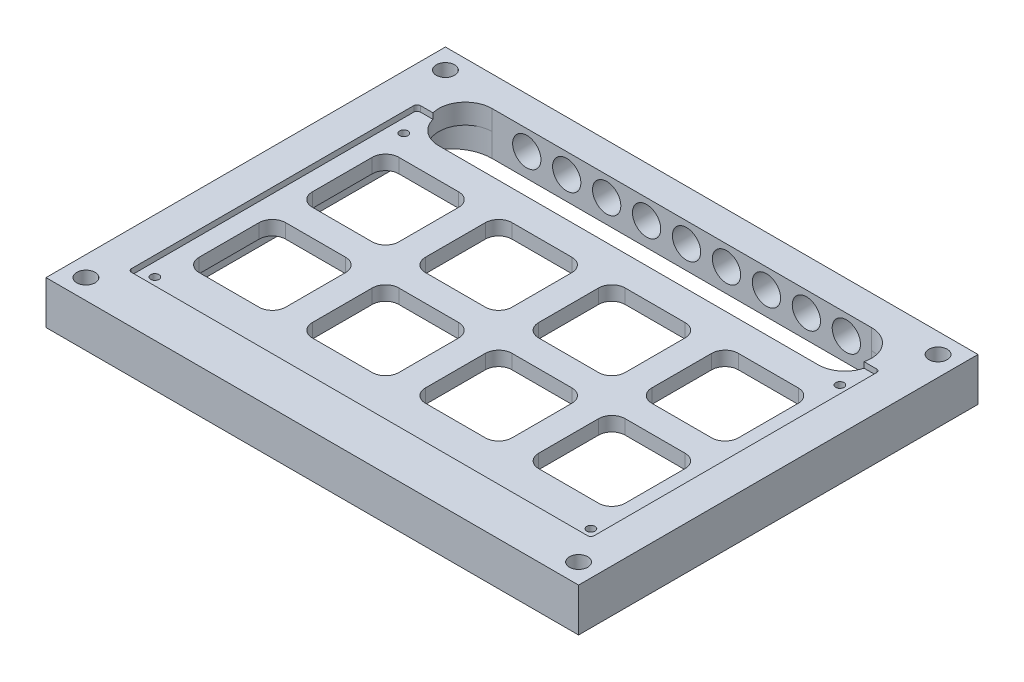
SolidWorks part; units mm, degrees
ref_plane "Plan de face" through (0, 0, 0) normal (0, 0, 1) x (1, 0, 0)
ref_plane "Plan de dessus" through (0, 0, 0) normal (0, 1, 0) x (1, 0, 0)
ref_plane "Plan de droite" through (0, 0, 0) normal (1, 0, 0) x (0, 0, -1)
sketch "Esquisse1" plane through (0, 0, 0) normal (0, 1, 0) x (1, 0, 0)
  line L1 (-145.1754, 42.9209) -> (14.8246, 42.9209)
  line L2 (-145.1754, 42.9209) -> (-145.1754, -77.0791)
  line L3 (-145.1754, -77.0791) -> (14.8246, -77.0791)
  line L4 (14.8246, 42.9209) -> (14.8246, -77.0791)
  dimension "D1" = 120
  dimension "D2" = 160
extrude "Boss.-Extru.1" add sketch "Esquisse1" along normal blind 13
sketch "Esquisse5" plane through (0, 0, -42.9209) normal (0, 0, -1) x (-1, 0, 0)
  line L0 (-14.8246, 13) -> (145.1754, 13) construction
  circle A0 centre (111.733, 7) radius 4.25
  circle A1 centre (99.733, 7) radius 4.25
  circle A2 centre (87.733, 7) radius 4.25
  circle A3 centre (75.733, 7) radius 4.25
  circle A4 centre (63.733, 7) radius 4.25
  circle A5 centre (51.733, 7) radius 4.25
  circle A6 centre (39.733, 7) radius 4.25
  circle A7 centre (27.733, 7) radius 4.25
  circle A8 centre (15.733, 7) radius 4.25
  dimension "D1" = 9
  dimension "D2" = 6
extrude "Enlèv. mat.-Extru.2" cut sketch "Esquisse5" against normal blind 12
sketch "Esquisse11" plane through (0, 0, 0) normal (0, -1, 0) x (1, 0, 0)
  line L0 (-145.1754, -42.9209) -> (-145.1754, 77.0791) construction
  line L1 (14.8246, -42.9209) -> (-145.1754, -42.9209) construction
  line B0 (-126.1754, 71.0791) -> (-4.1754, 71.0791)
  line B1 (-140.1754, 57.0791) -> (-140.1754, -24.9209)
  line B2 (-126.1754, -38.9209) -> (-4.1754, -38.9209)
  line B3 (9.8246, 57.0791) -> (9.8246, -24.9209)
  line B4 (-137.1754, 57.0791) -> (-137.1754, -24.9209)
  line B5 (-126.1754, -35.9209) -> (-4.1754, -35.9209)
  line B6 (6.8246, 57.0791) -> (6.8246, -24.9209)
  line B7 (-126.1754, 68.0791) -> (-4.1754, 68.0791)
  arc B8 (-4.1754, 71.0791) -> (9.8246, 57.0791) centre (-4.1754, 57.0791) cw
  arc B9 (-4.1754, -38.9209) -> (9.8246, -24.9209) centre (-4.1754, -24.9209) ccw
  arc B10 (-140.1754, -24.9209) -> (-126.1754, -38.9209) centre (-126.1754, -24.9209) ccw
  arc B11 (-126.1754, 71.0791) -> (-140.1754, 57.0791) centre (-126.1754, 57.0791) ccw
  arc B12 (-126.1754, 68.0791) -> (-137.1754, 57.0791) centre (-126.1754, 57.0791) ccw
  arc B13 (-137.1754, -24.9209) -> (-126.1754, -35.9209) centre (-126.1754, -24.9209) ccw
  arc B14 (-4.1754, -35.9209) -> (6.8246, -24.9209) centre (-4.1754, -24.9209) ccw
  arc B15 (-4.1754, 68.0791) -> (6.8246, 57.0791) centre (-4.1754, 57.0791) cw
  dimension "D1" = 5
  dimension "D2" = 4
sketch_block_instance "Bloc2-1"
sketch_block "Bloc2" parameters "D1"=14
extrude "Enlèv. mat.-Extru.6" cut sketch "Esquisse11" against normal blind 2
sketch "Esquisse4" plane through (0, 0, 0) normal (0, -1, 0) x (1, 0, 0)
  line L1 (-122.1754, 65.0791) -> (-8.1754, 65.0791)
  line L2 (-134.1754, 53.0791) -> (-134.1754, -21.9209)
  line L3 (-122.1754, -33.9209) -> (-8.1754, -33.9209)
  line L4 (3.8246, 53.0791) -> (3.8246, -21.9209)
  line L8 (-4.1754, 68.0791) -> (-126.1754, 68.0791) construction
  line L9 (-137.1754, 57.0791) -> (-137.1754, -24.9209) construction
  line L10 (-126.1754, -35.9209) -> (-4.1754, -35.9209) construction
  line L11 (6.8246, -24.9209) -> (6.8246, 57.0791) construction
  arc A0 (-122.1754, 65.0791) -> (-134.1754, 53.0791) centre (-122.1754, 53.0791) ccw
  arc A1 (-8.1754, 65.0791) -> (3.8246, 53.0791) centre (-8.1754, 53.0791) cw
  arc A2 (-8.1754, -33.9209) -> (3.8246, -21.9209) centre (-8.1754, -21.9209) ccw
  arc A3 (-134.1754, -21.9209) -> (-122.1754, -33.9209) centre (-122.1754, -21.9209) ccw
  dimension "D4" = 12
  dimension "D1" = 3
  dimension "D2" = 3
  dimension "D3" = 3
  dimension "D5" = 2
extrude "Enlèv. mat.-Extru.1" cut sketch "Esquisse4" against normal blind 7
sketch "Esquisse6" plane through (0, 7, 0) normal (0, -1, 0) x (1, 0, 0)
  line L0 (-91.1754, 25.0791) -> (-73.1754, 25.0791)
  line L1 (-125.1754, 51.0791) -> (-107.1754, 51.0791)
  line L2 (-129.1754, 47.0791) -> (-129.1754, 29.0791)
  line L3 (-125.1754, 25.0791) -> (-107.1754, 25.0791)
  line L4 (-103.1754, 47.0791) -> (-103.1754, 29.0791)
  line L5 (-95.1754, 47.0791) -> (-95.1754, 29.0791)
  line L6 (-91.1754, 51.0791) -> (-73.1754, 51.0791)
  line L7 (-69.1754, 47.0791) -> (-69.1754, 29.0791)
  line L8 (-57.1754, 25.0791) -> (-39.1754, 25.0791)
  line L9 (-61.1754, 47.0791) -> (-61.1754, 29.0791)
  line L10 (-57.1754, 51.0791) -> (-39.1754, 51.0791)
  line L11 (-35.1754, 47.0791) -> (-35.1754, 29.0791)
  line L12 (-23.1754, 25.0791) -> (-5.1754, 25.0791)
  line L13 (-27.1754, 47.0791) -> (-27.1754, 29.0791)
  line L14 (-23.1754, 51.0791) -> (-5.1754, 51.0791)
  line L15 (-1.1754, 47.0791) -> (-1.1754, 29.0791)
  line L16 (-91.1754, -8.9209) -> (-73.1754, -8.9209)
  line L17 (-95.1754, 13.0791) -> (-95.1754, -4.9209)
  line L18 (-91.1754, 17.0791) -> (-73.1754, 17.0791)
  line L19 (-69.1754, 13.0791) -> (-69.1754, -4.9209)
  line L20 (-57.1754, -8.9209) -> (-39.1754, -8.9209)
  line L21 (-61.1754, 13.0791) -> (-61.1754, -4.9209)
  line L22 (-57.1754, 17.0791) -> (-39.1754, 17.0791)
  line L23 (-35.1754, 13.0791) -> (-35.1754, -4.9209)
  line L24 (-23.1754, -8.9209) -> (-5.1754, -8.9209)
  line L25 (-27.1754, 13.0791) -> (-27.1754, -4.9209)
  line L26 (-23.1754, 17.0791) -> (-5.1754, 17.0791)
  line L27 (-1.1754, 13.0791) -> (-1.1754, -4.9209)
  line L28 (-125.1754, -8.9209) -> (-107.1754, -8.9209)
  line L29 (-129.1754, 13.0791) -> (-129.1754, -4.9209)
  line L30 (-125.1754, 17.0791) -> (-107.1754, 17.0791)
  line L31 (-103.1754, 13.0791) -> (-103.1754, -4.9209)
  line L32 (-145.1754, -42.9209) -> (-145.1754, 77.0791) construction
  line L33 (-145.1754, 77.0791) -> (14.8246, 77.0791) construction
  arc A0 (-125.1754, 51.0791) -> (-129.1754, 47.0791) centre (-125.1754, 47.0791) ccw
  arc A1 (-129.1754, 29.0791) -> (-125.1754, 25.0791) centre (-125.1754, 29.0791) ccw
  arc A2 (-107.1754, 25.0791) -> (-103.1754, 29.0791) centre (-107.1754, 29.0791) ccw
  arc A3 (-107.1754, 51.0791) -> (-103.1754, 47.0791) centre (-107.1754, 47.0791) cw
  arc A4 (-107.1754, -8.9209) -> (-103.1754, -4.9209) centre (-107.1754, -4.9209) ccw
  arc A5 (-125.1754, -8.9209) -> (-129.1754, -4.9209) centre (-125.1754, -4.9209) cw
  arc A6 (-129.1754, 13.0791) -> (-125.1754, 17.0791) centre (-125.1754, 13.0791) cw
  arc A7 (-107.1754, 17.0791) -> (-103.1754, 13.0791) centre (-107.1754, 13.0791) cw
  arc A8 (-91.1754, -8.9209) -> (-95.1754, -4.9209) centre (-91.1754, -4.9209) cw
  arc A9 (-95.1754, 13.0791) -> (-91.1754, 17.0791) centre (-91.1754, 13.0791) cw
  arc A10 (-73.1754, 17.0791) -> (-69.1754, 13.0791) centre (-73.1754, 13.0791) cw
  arc A11 (-73.1754, -8.9209) -> (-69.1754, -4.9209) centre (-73.1754, -4.9209) ccw
  arc A12 (-57.1754, -8.9209) -> (-61.1754, -4.9209) centre (-57.1754, -4.9209) cw
  arc A13 (-61.1754, 13.0791) -> (-57.1754, 17.0791) centre (-57.1754, 13.0791) cw
  arc A14 (-39.1754, 17.0791) -> (-35.1754, 13.0791) centre (-39.1754, 13.0791) cw
  arc A15 (-39.1754, -8.9209) -> (-35.1754, -4.9209) centre (-39.1754, -4.9209) ccw
  arc A16 (-23.1754, -8.9209) -> (-27.1754, -4.9209) centre (-23.1754, -4.9209) cw
  arc A17 (-5.1754, -8.9209) -> (-1.1754, -4.9209) centre (-5.1754, -4.9209) ccw
  arc A18 (-5.1754, 17.0791) -> (-1.1754, 13.0791) centre (-5.1754, 13.0791) cw
  arc A19 (-27.1754, 13.0791) -> (-23.1754, 17.0791) centre (-23.1754, 13.0791) cw
  arc A20 (-5.1754, 25.0791) -> (-1.1754, 29.0791) centre (-5.1754, 29.0791) ccw
  arc A21 (-5.1754, 51.0791) -> (-1.1754, 47.0791) centre (-5.1754, 47.0791) cw
  arc A22 (-27.1754, 47.0791) -> (-23.1754, 51.0791) centre (-23.1754, 47.0791) cw
  arc A23 (-23.1754, 25.0791) -> (-27.1754, 29.0791) centre (-23.1754, 29.0791) cw
  arc A24 (-39.1754, 25.0791) -> (-35.1754, 29.0791) centre (-39.1754, 29.0791) ccw
  arc A25 (-39.1754, 51.0791) -> (-35.1754, 47.0791) centre (-39.1754, 47.0791) cw
  arc A26 (-61.1754, 47.0791) -> (-57.1754, 51.0791) centre (-57.1754, 47.0791) cw
  arc A27 (-57.1754, 25.0791) -> (-61.1754, 29.0791) centre (-57.1754, 29.0791) cw
  arc A28 (-91.1754, 25.0791) -> (-95.1754, 29.0791) centre (-91.1754, 29.0791) cw
  arc A29 (-73.1754, 25.0791) -> (-69.1754, 29.0791) centre (-73.1754, 29.0791) ccw
  arc A30 (-73.1754, 51.0791) -> (-69.1754, 47.0791) centre (-73.1754, 47.0791) cw
  arc A31 (-95.1754, 47.0791) -> (-91.1754, 51.0791) centre (-91.1754, 47.0791) cw
  point P36 (-129.1754, 25.0791)
  point P39 (-103.1754, 25.0791)
  point P42 (-103.1754, 51.0791)
  dimension "D5" = 4
  dimension "D6" = 4
  dimension "D1" = 26
  dimension "D2" = 26
  dimension "D7" = 16
  dimension "D8" = 26
  dimension "D9" = 34
  dimension "D10" = 34
  dimension "D3" = 4
  dimension "D4" = 2
extrude "Enlèv. mat.-Extru.3" cut sketch "Esquisse6" against normal through all
sketch "Esquisse8" plane through (0, 7, 0) normal (0, -1, 0) x (1, 0, 0)
  line L0 (-122.1754, -25.9209) -> (-8.1754, -25.9209) construction
  line L1 (-122.1754, -17.9209) -> (-8.1754, -17.9209)
  line L2 (-122.1754, -33.9209) -> (-8.1754, -33.9209)
  line L3 (-122.1754, -33.9209) -> (-115.983, -33.9209) construction
  line L4 (-134.1754, 53.0791) -> (-134.1754, -21.9209) construction
  line L5 (3.8246, -21.9209) -> (3.8246, 53.0791) construction
  arc A0 (-122.1754, -17.9209) -> (-122.1754, -33.9209) centre (-122.1754, -25.9209) ccw
  arc A1 (-8.1754, -33.9209) -> (-8.1754, -17.9209) centre (-8.1754, -25.9209) ccw
  point P2 (-65.1754, -25.9209)
  dimension "D1" = 8
  dimension "D2" = 8
  dimension "D3" = 12
  dimension "D4" = 12
extrude "Enlèv. mat.-Extru.5" cut sketch "Esquisse8" against normal through all
hole_wizard "Dégagement M51" positions "Esquisse9" profile "Esquisse10" hole size "M5" standard "ISO" end condition through all
sketch "Esquisse9" plane through (0, 0, 0) normal (0, -1, 0) x (-1, 0, 0)
  line L0 (-14.8246, 42.9209) -> (145.1754, 42.9209) construction
  line L1 (145.1754, 42.9209) -> (145.1754, -77.0791) construction
  line L2 (145.1754, -77.0791) -> (-14.8246, -77.0791) construction
  line L3 (-14.8246, -77.0791) -> (-14.8246, 42.9209) construction
  point P0 (139.1754, 36.9209)
  point P2 (139.1754, -71.0791)
  point P4 (-8.8246, -71.0791)
  point P6 (-8.8246, 36.9209)
  dimension "D1" = 6
  dimension "D2" = 6
  dimension "D3" = 6
  dimension "D4" = 6
  dimension "D5" = 6
  dimension "D6" = 6
  dimension "D7" = 6
  dimension "D8" = 6
sketch "Esquisse10" plane through (-139.1754, 0, -36.9209) normal (1, 0, 0) x (0, 0, -1)
  line L0 (0, 0) -> (0, 13)
  line L1 (0, 13) -> (2.75, 13)
  line L2 (2.75, 13) -> (2.75, 0)
  line L5 (2.75, 0) -> (0, 0)
  line L11 (0, -6.35) -> (0, 107.95) construction
  dimension "Diamètre du perçage jusqu'au prochain" = 5.5
  dimension "Profondeur du perçage jusqu'au prochain" = 13
sketch "Esquisse12" plane through (0, 13, 0) normal (0, 1, 0) x (1, 0, 0)
  line L0 (14.8246, -77.0791) -> (14.8246, 42.9209) construction
  line L1 (3.3246, -61.8791) -> (-133.6754, -61.8791)
  line L2 (3.3246, -61.8791) -> (3.3246, 16.9209)
  line L3 (3.3246, 16.9209) -> (-133.6754, 16.9209)
  line L4 (-133.6754, -61.8791) -> (-133.6754, 16.9209)
  line L5 (-5.1754, -51.0791) -> (-23.1754, -51.0791) construction
  dimension "D1" = 137
  dimension "D2" = 78.8
  dimension "D3" = 11.5
  dimension "D4" = 10.8
sketch "Esquisse13" plane through (0, 13, 0) normal (0, 1, 0) x (1, 0, 0)
  line L0 (3.3246, -61.8791) -> (-133.6754, -61.8791) construction
  line L1 (3.3246, -62.8791) -> (-133.6754, -62.8791)
  line L2 (4.3246, -61.8791) -> (4.3246, 22.9209)
  line L3 (3.3246, 23.9209) -> (-133.6754, 23.9209)
  line L4 (-134.6754, -61.8791) -> (-134.6754, 22.9209)
  line L5 (3.3246, -61.8791) -> (3.3246, 16.9209) construction
  line L6 (-133.6754, -61.8791) -> (-133.6754, 16.9209) construction
  line L7 (3.3246, 16.9209) -> (-133.6754, 16.9209) construction
  arc A0 (3.3246, -62.8791) -> (4.3246, -61.8791) centre (3.3246, -61.8791) ccw
  arc A1 (-133.6754, -62.8791) -> (-134.6754, -61.8791) centre (-133.6754, -61.8791) cw
  arc A2 (-133.6754, 23.9209) -> (-134.6754, 22.9209) centre (-133.6754, 22.9209) ccw
  arc A3 (4.3246, 22.9209) -> (3.3246, 23.9209) centre (3.3246, 22.9209) ccw
  dimension "D5" = 1
  dimension "D6" = 1
  dimension "D1" = 1
  dimension "D2" = 1
  dimension "D3" = 1
  dimension "D4" = 7
extrude "Enlèv. mat.-Extru.7" cut sketch "Esquisse13" against normal blind 1.7
hole_wizard "Trou pour taraudage pour trou taraudé M31" positions "Esquisse14" profile "Esquisse15" hole size "M3" standard "ISO"
sketch "Esquisse14" plane through (0, 11.3, 0) normal (0, 1, 0) x (1, 0, 0)
  line L0 (3.3246, -61.8791) -> (-133.6754, -61.8791) construction
  line L1 (-133.6754, -61.8791) -> (-133.6754, 16.9209) construction
  line L2 (3.3246, 16.9209) -> (-133.6754, 16.9209) construction
  line L3 (3.3246, -61.8791) -> (3.3246, 16.9209) construction
  point P0 (0.3246, -58.8791)
  point P2 (-130.6754, -58.8791)
  point P4 (-130.6754, 15.9209)
  point P6 (0.3246, 15.9209)
  dimension "D1" = 3
  dimension "D2" = 3
  dimension "D3" = 1
  dimension "D4" = 3
  dimension "D5" = 3
  dimension "D6" = 1
  dimension "D7" = 3
  dimension "D8" = 3
sketch "Esquisse15" plane through (0.3246, 11.3, 58.8791) normal (1, 0, 0) x (0, 0, 1)
  line L0 (0, 0) -> (0, 3.7511)
  line L1 (0, 3.7511) -> (1.25, 3)
  line L2 (1.25, 3) -> (1.25, 0)
  line L5 (1.25, 0) -> (0, 0)
  line L10 (0, 3.7511) -> (-1.25, 3) construction
  line L11 (0, -6.35) -> (0, 107.95) construction
  dimension "Diamètre du perçage" = 2.5
  dimension "Profondeur du perçage" = 3
  dimension "Angle de pointe" = 118
sketch "Esquisse16" plane through (0, 13, 0) normal (0, 1, 0) x (1, 0, 0)
  line L0 (14.8246, -77.0791) -> (14.8246, 42.9209) construction
  line L1 (-145.1754, -77.0791) -> (14.8246, -77.0791) construction
  line B0 (-126.1754, 37.9209) -> (-4.1754, 37.9209)
  line B1 (-140.1754, 23.9209) -> (-140.1754, -58.0791)
  line B2 (-126.1754, -72.0791) -> (-4.1754, -72.0791)
  line B3 (9.8246, 23.9209) -> (9.8246, -58.0791)
  line B4 (-137.1754, 23.9209) -> (-137.1754, -58.0791)
  line B5 (-126.1754, -69.0791) -> (-4.1754, -69.0791)
  line B6 (6.8246, 23.9209) -> (6.8246, -58.0791)
  line B7 (-126.1754, 34.9209) -> (-4.1754, 34.9209)
  arc B8 (-4.1754, 37.9209) -> (9.8246, 23.9209) centre (-4.1754, 23.9209) cw
  arc B9 (-4.1754, -72.0791) -> (9.8246, -58.0791) centre (-4.1754, -58.0791) ccw
  arc B10 (-140.1754, -58.0791) -> (-126.1754, -72.0791) centre (-126.1754, -58.0791) ccw
  arc B11 (-126.1754, 37.9209) -> (-140.1754, 23.9209) centre (-126.1754, 23.9209) ccw
  arc B12 (-126.1754, 34.9209) -> (-137.1754, 23.9209) centre (-126.1754, 23.9209) ccw
  arc B13 (-137.1754, -58.0791) -> (-126.1754, -69.0791) centre (-126.1754, -58.0791) ccw
  arc B14 (-4.1754, -69.0791) -> (6.8246, -58.0791) centre (-4.1754, -58.0791) ccw
  arc B15 (-4.1754, 34.9209) -> (6.8246, 23.9209) centre (-4.1754, 23.9209) cw
  dimension "D1" = 5
  dimension "D2" = 5
sketch_block_instance "Bloc3-1"
sketch_block "Bloc3" parameters "D1"=14
